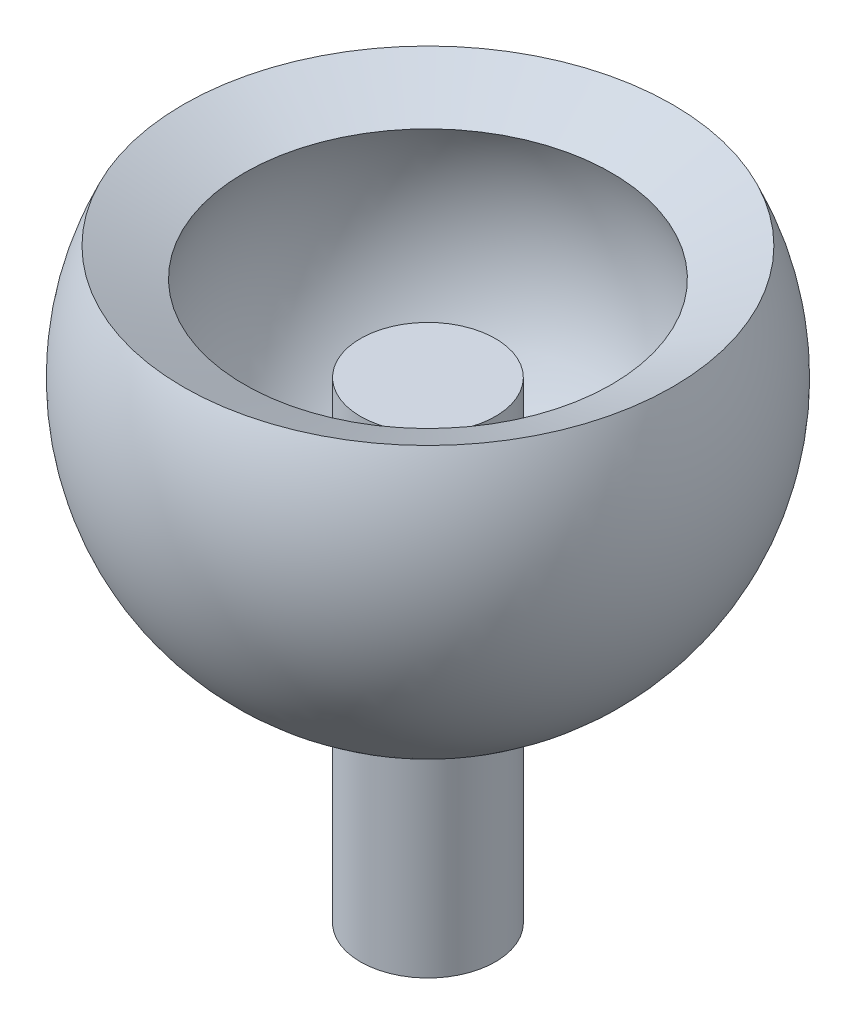
SolidWorks part; units mm, degrees
ref_plane "Plan de face" through (0, 0, 0) normal (0, 0, 1) x (1, 0, 0)
ref_plane "Plan de dessus" through (0, 0, 0) normal (0, 1, 0) x (1, 0, 0)
ref_plane "Plan de droite" through (0, 0, 0) normal (1, 0, 0) x (0, 0, -1)
sketch "Esquisse1" plane through (0, 0, 0) normal (0, 0, 1) x (1, 0, 0)
  line L0 (0, 0) -> (0, -12.9952) construction
  line L1 (0, 0) -> (0, -17.2806) construction
  line L2 (0, 0) -> (-10.8757, 5.0714) construction
  line L3 (-7.2505, 3.3809) -> (-5.4378, 2.5357)
  line L4 (0, 0) -> (10.4471, 0) construction
  line L5 (0, -6) -> (0, -8)
  arc A0 (-5.4378, 2.5357) -> (0, -6) centre (0, 0) ccw
  arc A1 (-7.2505, 3.3809) -> (0, -8) centre (0, 0) ccw
  dimension "D1" = 6
  dimension "D2" = 8
  dimension "D3" = 155
revolve "Révolution1" add sketch "Esquisse1" angle 360 about L0
sketch "Esquisse2" plane through (0, 0, 0) normal (0, 1, 0) x (1, 0, 0)
  circle A0 centre (0, 0) radius 2
  dimension "D1" = 4
extrude "Boss.-Extru.1" add sketch "Esquisse2" against normal blind 14
